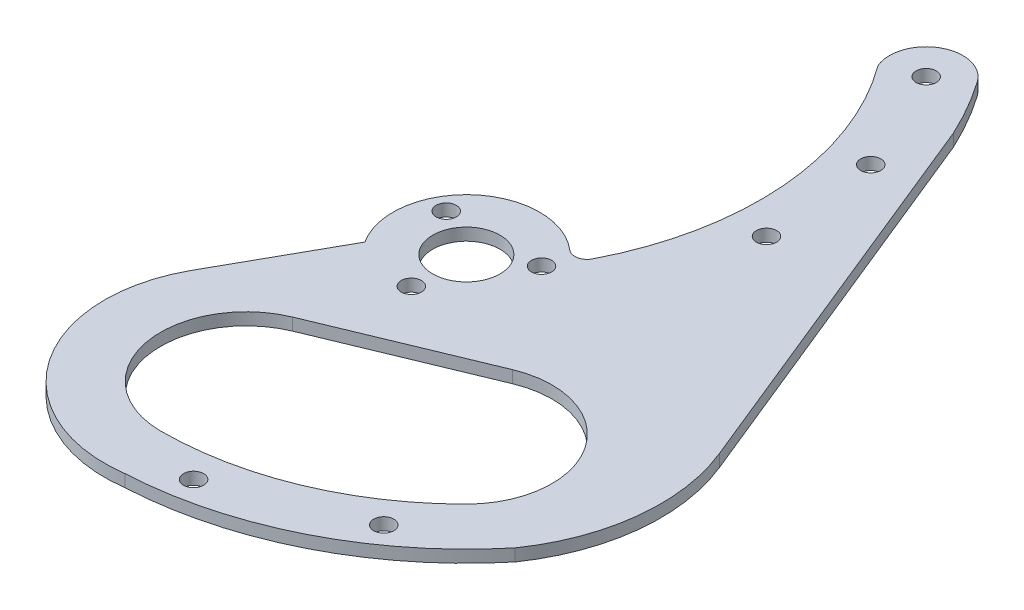
SolidWorks part; units mm, degrees
ref_plane "Спереди" through (0, 0, 0) normal (0, 0, 1) x (1, 0, 0)
ref_plane "Сверху" through (0, 0, 0) normal (0, 1, 0) x (1, 0, 0)
ref_plane "Справа" through (0, 0, 0) normal (1, 0, 0) x (0, 0, -1)
sketch "Эскиз1" plane through (0, 0, 0) normal (0, 1, 0) x (1, 0, 0)
  line L0 (0, 0) -> (0, -55) construction
  line L1 (9.5506, -54.1644) -> (0, 0) construction
  line L2 (0, 0) -> (35.7004, -86.1885) construction
  line L3 (0, 0) -> (0, 63.6396) construction
  line L4 (-31.8198, 31.8198) -> (11.2518, 74.8914) construction
  line L5 (22.6306, 57.0221) -> (48.8691, -7.4755)
  line L6 (0, -50) -> (0, -22) construction
  line L7 (0, 0) -> (38.8909, -38.8909) construction
  line L8 (0, 0) -> (-20.1763, 11.6488) construction
  line L9 (0, 0) -> (0, -14.3061) construction
  line L10 (0, 0) -> (20.2825, 11.7101) construction
  line L11 (-31.8198, 31.8198) -> (0, 0) construction
  line L12 (-5.3576, -23.0657) -> (20.0983, -12.5215)
  line L14 (-31.8198, 31.8198) -> (0, 63.6396) construction
  line L15 (-10.0655, -6.5335) -> (-20.2182, -24.7016)
  line L16 (35.3553, -35.3553) -> (15.5563, -15.5563) construction
  line L18 (-31.8198, 31.8198) -> (31.5399, 76.1847) construction
  arc A0 (45.5387, -37.561) -> (3.1421, -58.9468) centre (0, 0) cw
  arc A1 (0, -50) -> (35.3553, -35.3553) centre (0, 0) ccw
  arc A2 (0, -55) -> (55, 0) centre (0, 0) ccw construction
  circle A3 centre (9.5506, -54.1644) radius 1.65
  circle A4 centre (31.5467, -45.0534) radius 1.65
  arc A5 (6.9073, 60.4114) -> (9.5698, 7.24) centre (-31.8198, 31.8198) cw
  circle A6 centre (0, 0) radius 5.5
  arc A7 (17.3293, 66.2344) -> (22.6306, 57.0221) centre (-31.8198, 31.8198) cw
  arc A8 (17.7007, 53.354) -> (11.5936, 63.9334) centre (-31.8198, 31.8198) ccw construction
  arc A9 (-3.7011, -11.415) -> (2.0838, -11.8177) centre (0, 0) ccw construction
  arc A10 (17.3293, 66.2344) -> (6.9073, 60.4114) centre (12.4144, 62.7929) ccw
  arc A11 (35.3553, -35.3553) -> (20.0983, -12.5215) centre (25.4558, -25.4558) ccw
  arc A12 (45.5387, -37.561) -> (48.8691, -7.4755) centre (19.4454, -19.4454) ccw
  circle A13 centre (0, 0) radius 9 construction
  circle A14 centre (0, -9) radius 1.65
  circle A15 centre (-7.7942, 4.5) radius 1.65
  circle A17 centre (0, 0) radius 10.65 construction
  arc A18 (0, -50) -> (-5.3576, -23.0657) centre (0, -36) cw
  circle A19 centre (7.7942, 4.5) radius 1.65
  arc A20 (0, 0) -> (-4.1195, -3.6442) centre (-31.8198, 31.8198) ccw construction
  circle A21 centre (0, -36) radius 14 construction
  arc A22 (9.5698, 7.24) -> (-10.0655, -6.5335) centre (0, 0) ccw
  arc A23 (3.1421, -58.9468) -> (-20.2182, -24.7016) centre (0, -36) cw
  dimension "D2" = 55
  dimension "D3" = 50
  dimension "D4" = 3.3
  dimension "D7" = 90
  dimension "D8" = 12
  dimension "D9" = 11
  dimension "D10" = 90
  dimension "D11" = 18
  dimension "D12" = 28
  dimension "D13" = 21.3
  dimension "D14" = 120
  dimension "D20" = 23.161
  dimension "D16" = 28
  dimension "D17" = 12
  dimension "D18" = 10
  dimension "D19" = 54
  dimension "D5" = 10
  dimension "D6" = 22.5
  dimension "D15" = 120
extrude "Бобышка-Вытянуть1" add sketch "Эскиз1" along normal blind 2
sketch "Эскиз2" plane through (0, 0, 0) normal (0, -1, 0) x (1, 0, 0)
  line L0 (-31.8198, -31.8198) -> (0, 0) construction
  line L1 (-31.8198, -31.8198) -> (22.9872, -27.0248) construction
  line L2 (-31.8198, -31.8198) -> (13.7419, -63.7224) construction
  line L3 (-31.8198, -31.8198) -> (22.5978, -46.401) construction
  circle A0 centre (21.9747, -27.1134) radius 1.65
  circle A1 centre (12.4144, -62.7929) radius 1.65
  circle A2 centre (20.3402, -45.796) radius 1.65
  circle A3 centre (-31.8198, -31.8198) radius 54 construction
  point P0 (-31.8198, -31.8198)
  dimension "D3" = 3.3
  dimension "D4" = 3.3
  dimension "D5" = 3.3
  dimension "D1" = 40
  dimension "D2" = 60
  dimension "D6" = 80
extrude "Вырез-Вытянуть1" cut sketch "Эскиз2" against normal through all
fillet "Скругление1" radius 2 1 edges at (9.5698, 1, -7.24)
